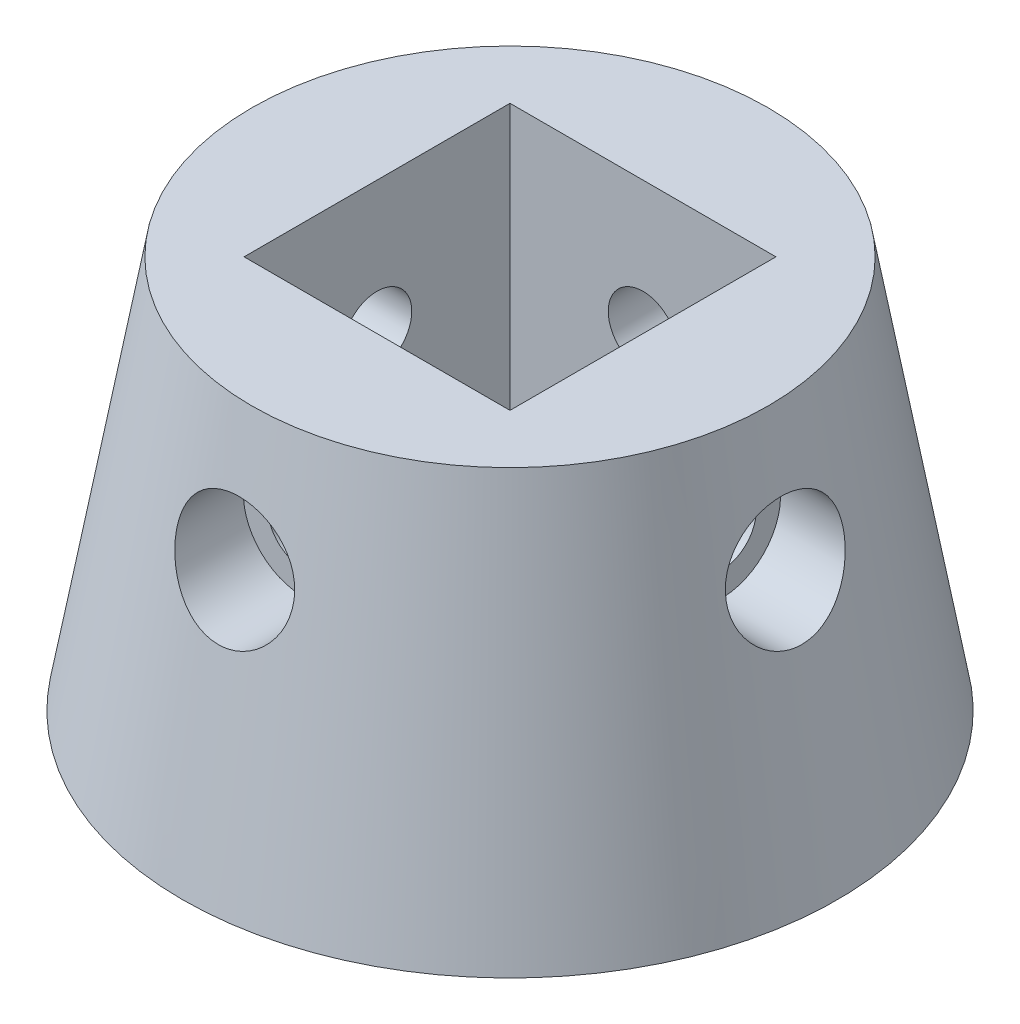
SolidWorks part; units mm, degrees
ref_plane "前视基准面" through (0, 0, 0) normal (0, 0, 1) x (1, 0, 0)
ref_plane "上视基准面" through (0, 0, 0) normal (0, 1, 0) x (1, 0, 0)
ref_plane "右视基准面" through (0, 0, 0) normal (1, 0, 0) x (0, 0, -1)
sketch "草图1" plane through (0, 0, 0) normal (0, 1, 0) x (1, 0, 0)
  circle A0 centre (0, 0) radius 25
  dimension "D1" = 50
extrude "凸台-拉伸1" add sketch "草图1" along normal blind 30 draft 10
sketch "草图3" plane through (0, 30, 0) normal (0, 1, 0) x (1, 0, 0)
  line L1 (-10.15, 10.15) -> (10.15, 10.15)
  line L2 (-10.15, 10.15) -> (-10.15, -10.15)
  line L3 (-10.15, -10.15) -> (10.15, -10.15)
  line L4 (10.15, 10.15) -> (10.15, -10.15)
  line L5 (0, -10.15) -> (0, 10.15) construction
  line L6 (-10.15, 0) -> (10.15, 0) construction
  point P0 (0, 0)
  dimension "D1" = 20.3
  dimension "D2" = 20.3
extrude "切除-拉伸2" cut sketch "草图3" against normal through all
sketch "草图4" plane through (-10.15, 0, 0) normal (1, 0, 0) x (0, 0, -1)
  line L0 (-10.15, 30) -> (10.15, 30) construction
  circle A0 centre (0, 20) radius 2.65
  dimension "D1" = 5.3
  dimension "D2" = 10
extrude "切除-拉伸3" cut sketch "草图4" against normal through all and the other way through all
sketch "草图5" plane through (0, 0, 10.15) normal (0, 0, -1) x (-1, 0, 0)
  line L0 (19.7102, 30) -> (-19.7102, 30) construction
  circle A0 centre (0, 20) radius 2.65
  dimension "D1" = 5.3
  dimension "D2" = 10
extrude "切除-拉伸4" cut sketch "草图5" against normal through all and the other way through all
ref_plane "基准面1" through (0, 0, -20.15) normal (0, 0, 1) x (1, 0, 0)
sketch "草图6" plane through (0, 0, -20.15) normal (0, 0, 1) x (1, 0, 0)
  circle A0 centre (0, 20) radius 4.5
  dimension "D1" = 9
extrude "切除-拉伸5" cut sketch "草图6" against normal blind 15 and the other way blind 4
ref_plane "基准面2" through (20.15, 0, 0) normal (-1, 0, 0) x (0, 0, 1)
sketch "草图7" plane through (20.15, 0, 0) normal (-1, 0, 0) x (0, 0, 1)
  circle A0 centre (0, 20) radius 4.5
  dimension "D1" = 9
extrude "切除-拉伸6" cut sketch "草图7" against normal blind 15 and the other way blind 4
ref_plane "基准面3" through (0.15, 0, 0) normal (-1, 0, 0) x (0, 0, 1)
mirror "镜向1" about plane through (0.15, 0, 0) normal (-1, 0, 0) of "切除-拉伸6"
ref_plane "基准面4" through (0, 0, -0.15) normal (0, 0, 1) x (1, 0, 0)
mirror "镜向2" about plane through (0, 0, -0.15) normal (0, 0, 1) of "切除-拉伸5"
